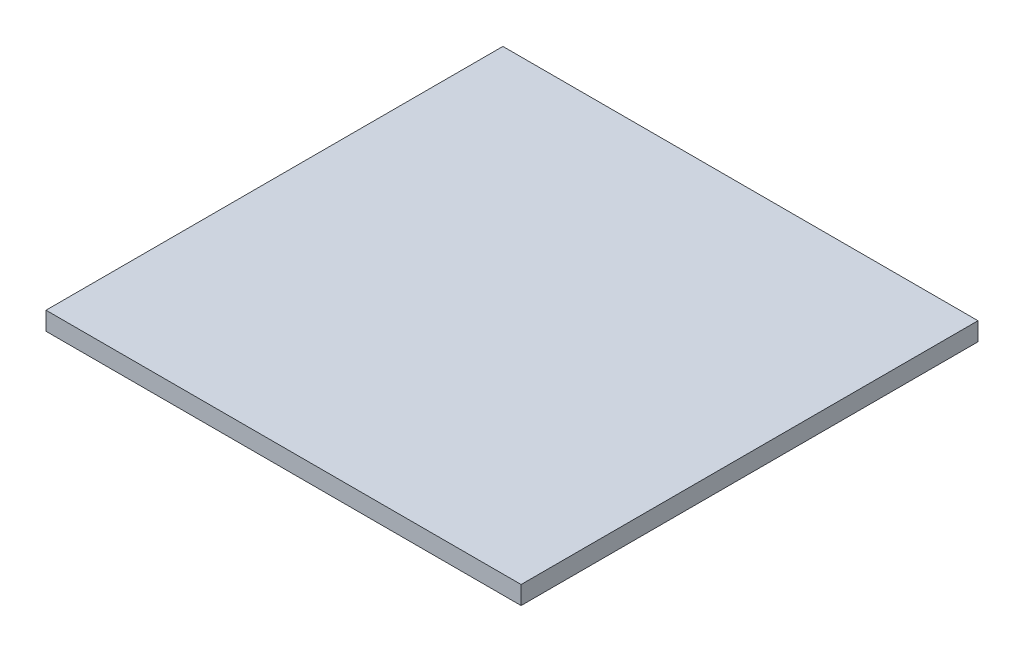
SolidWorks part; units mm, degrees
ref_plane "Front Plane" through (0, 0, 0) normal (0, 0, 1) x (1, 0, 0)
ref_plane "Top Plane" through (0, 0, 0) normal (0, 1, 0) x (1, 0, 0)
ref_plane "Right Plane" through (0, 0, 0) normal (1, 0, 0) x (0, 0, -1)
sketch "Sketch1" plane through (0, 0, 0) normal (0, 1, 0) x (1, 0, 0)
  line L1 (0, 0) -> (-660.4, 0)
  line L2 (0, 0) -> (0, 635.0921)
  line L3 (0, 635.0921) -> (-660.4, 635.0921)
  line L4 (-660.4, 0) -> (-660.4, 635.0921)
  dimension "D1" = 660.4
  dimension "D2" = 635.0921
extrude "Boss-Extrude1" add sketch "Sketch1" along normal blind 25.4
